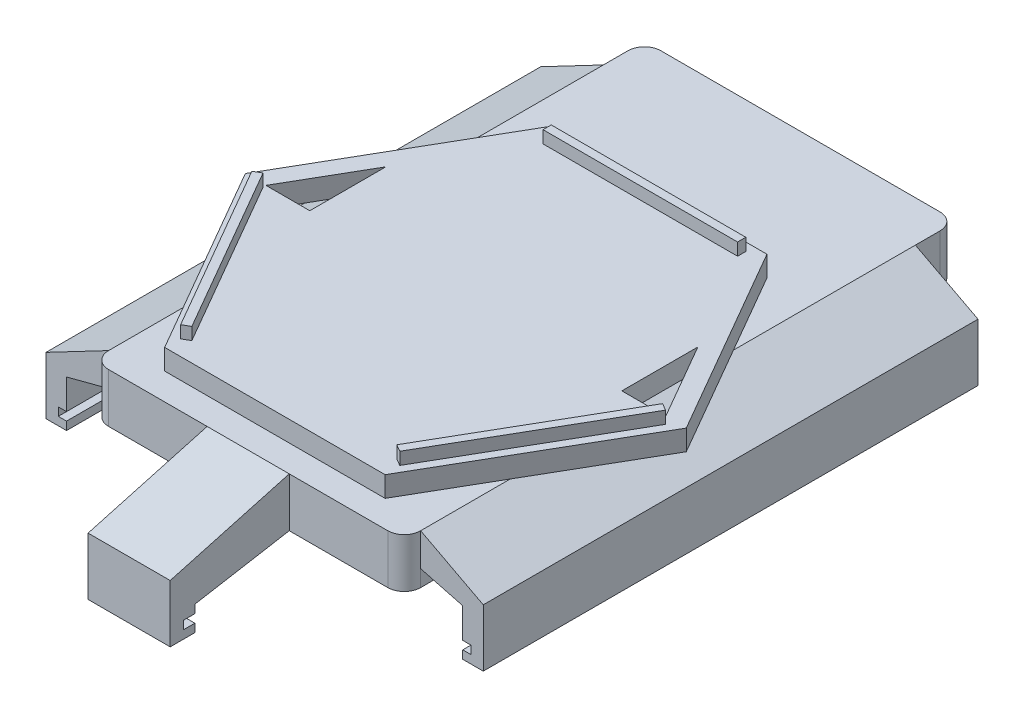
SolidWorks part; units mm, degrees
ref_plane "Plano frontal" through (0, 0, 0) normal (0, 0, 1) x (1, 0, 0)
ref_plane "Plano superior" through (0, 0, 0) normal (0, 1, 0) x (1, 0, 0)
ref_plane "Plano direito" through (0, 0, 0) normal (1, 0, 0) x (0, 0, -1)
sketch "Esboço1" plane through (0, 0, 0) normal (0, 1, 0) x (1, 0, 0)
  line L7 (53.6936, 0) -> (26.8468, 46.5)
  line L8 (26.8468, 46.5) -> (-26.8468, 46.5)
  line L9 (-26.8468, 46.5) -> (-53.6936, 0)
  line L10 (-53.6936, 0) -> (-26.8468, -46.5)
  line L11 (-26.8468, -46.5) -> (26.8468, -46.5)
  line L12 (26.8468, -46.5) -> (53.6936, 0)
  circle A1 centre (0, 0) radius 46.5 construction
extrude "Ressalto-extrusão1" add sketch "Esboço1" along normal blind 3
sketch "Esboço2" plane through (0, 3, 0) normal (0, 1, 0) x (1, 0, 0)
  line L2 (23.6921, 44.5) -> (-23.6921, 44.5)
  line L4 (-50.3842, -1.7321) -> (-26.6921, -42.7679)
  line L6 (26.6921, -42.7679) -> (50.3842, -1.7321)
  line L8 (-23.6921, 44.5) -> (-23.6921, 42.5)
  line L11 (23.6921, 44.5) -> (23.6921, 42.5)
  line L15 (50.3842, -1.7321) -> (48.6521, -0.7321)
  line L18 (26.6921, -42.7679) -> (24.96, -41.7679)
  line L20 (-48.6521, -0.7321) -> (-24.96, -41.7679)
  line L22 (-26.6921, -42.7679) -> (-24.96, -41.7679)
  line L25 (-50.3842, -1.7321) -> (-48.6521, -0.7321)
  line L36 (24.96, -41.7679) -> (48.6521, -0.7321)
  line L38 (23.6921, 42.5) -> (-23.6921, 42.5)
  line L40 (51.3842, 0) -> (25.6921, 44.5) [skipped]
  line L41 (-25.6921, 44.5) -> (-51.3842, 0) [skipped]
  line L42 (-25.6921, -44.5) -> (25.6921, -44.5) [skipped]
extrude "Ressalto-extrusão2" add sketch "Esboço2" along normal blind 3
sketch "Esboço3" plane through (0, 0, 0) normal (0, -1, 0) x (1, 0, 0)
  line L13 (26.8468, 46.5) -> (-26.8468, 46.5)
  line L14 (-26.8468, 46.5) -> (-53.6936, 0)
  line L15 (-53.6936, 0) -> (-26.8468, -46.5)
  line L16 (-26.8468, -46.5) -> (26.8468, -46.5)
  line L17 (26.8468, -46.5) -> (53.6936, 0)
  line L18 (53.6936, 0) -> (26.8468, 46.5)
  circle A0 centre (0, 0) radius 46.5 construction
extrude "Ressalto-extrusão3" add sketch "Esboço3" along normal blind 2
sketch "Esboço5" plane through (0, -2, 0) normal (0, -1, 0) x (1, 0, 0)
  line L1 (38, 49.0015) -> (38, -77.5)
  line L13 (-34, -81.5) -> (34, -81.5)
  line L15 (-34, 53.0015) -> (34, 53.0015)
  line L17 (-38, 49.0015) -> (-38, -77.5)
  arc A0 (38, 49.0015) -> (34, 53.0015) centre (34, 49.0015) ccw
  arc A1 (-34, 53.0015) -> (-38, 49.0015) centre (-34, 49.0015) ccw
  arc A2 (-38, -77.5) -> (-34, -81.5) centre (-34, -77.5) ccw
  arc A3 (34, -81.5) -> (38, -77.5) centre (34, -77.5) ccw
extrude "Ressalto-extrusão5" add sketch "Esboço5" along normal blind 12
sketch "Esboço7" plane through (0, 0, -81.5) normal (0, 0, -1) x (-1, 0, 0)
  line L6 (-34.2, -3) -> (34.2, -3)
  line L8 (-34.2, -3) -> (-34.2, -12.3)
  line L9 (34.2, -3) -> (34.2, -12.3)
  line L10 (31.2, -12.3) -> (34.2, -12.3)
  line L11 (-31.2, -12.3) -> (-34.2, -12.3)
  line L17 (-31.2, -26.2504) -> (31.2, -23.2814)
  line L18 (-31.2, -12.3) -> (-31.2, -26.2504)
  line L19 (31.2, -12.3) -> (31.2, -23.2814)
extrude "Corte-extrusão1" cut sketch "Esboço7" against normal blind 131
sketch "Esboço8" plane through (0, -2, 0) normal (0, -1, 0) x (1, 0, 0)
  line L6 (-48.6936, 0) -> (-38, 0)
  line L7 (38, 0) -> (48.6936, 0)
  line L8 (-48.6936, 0) -> (-38, -18.5218)
  line L10 (38, -18.5218) -> (48.6936, 0)
  line L12 (-38, 0) -> (-38, -18.5218)
  line L13 (38, 0) -> (38, -18.5218)
extrude "Corte-extrusão3" cut sketch "Esboço8" against normal blind 10
ref_plane "Plano3" through (0, 0, -71.5) normal (0, 0, -1) x (-1, 0, 0)
sketch "Esboço17" plane through (0, 0, -71.5) normal (0, 0, -1) x (-1, 0, 0)
  line L3 (-53.25, -20) -> (-53.25, -18)
  line L4 (-53.25, -18) -> (-53.25, -10)
  line L7 (-48.25, -18) -> (-48.25, -20)
  line L9 (53.25, -20) -> (53.25, -18)
  line L13 (48.25, -18) -> (48.25, -20)
  line L14 (53.25, -18) -> (53.25, -10)
  line L15 (-48.25, -22) -> (-48.25, -24)
  line L16 (48.25, -22) -> (48.25, -24)
  line L18 (-53.25, -20) -> (-53.25, -22)
  line L20 (-53.25, -22) -> (-53.25, -24)
  line L21 (-53.25, -24) -> (-48.25, -24)
  line L22 (48.25, -22) -> (48.25, -20)
  line L23 (53.25, -20) -> (53.25, -24)
  line L24 (48.25, -24) -> (53.25, -24)
  line L29 (-38, -6) -> (-38, -10)
  line L30 (38, -6) -> (38, -10)
  line L31 (-48.25, -22) -> (-48.25, -20)
  line L34 (-48.25, -12.6885) -> (-38, -10)
  line L35 (48.25, -12.6885) -> (38, -10)
  line L36 (-48.25, -18) -> (-48.25, -12.6885)
  line L37 (48.25, -18) -> (48.25, -12.6885)
  line L38 (53.25, -10) -> (38, -2)
  line L39 (38, -2) -> (38, -6)
  line L40 (-53.25, -10) -> (-38, -2)
  line L41 (-38, -2) -> (-38, -6)
extrude "Ressalto-extrusão13" add sketch "Esboço17" against normal blind 120.5
sketch "Esboço19" plane through (0, 0, 0) normal (1, 0, 0) x (0, 0, -1)
  line L0 (-53.0015, -14) -> (-53.0015, -2)
  line L1 (-76, -24) -> (-82, -24)
  line L2 (-82, -24) -> (-82, -10)
  line L4 (-82, -10) -> (-53.0015, -2)
  line L10 (-76, -24) -> (-76, -18)
  line L13 (-76, -18) -> (-53.0015, -14)
extrude "Ressalto-extrusão14" add sketch "Esboço19" along normal mid plane 20
sketch "Esboço20" plane through (0, 0, -71.5) normal (0, 0, -1) x (-1, 0, 0)
  line L2 (-50.25, -22) -> (50.25, -22)
  line L4 (-50.25, -20) -> (50.25, -20)
  line L7 (-50.25, -22) -> (-50.25, -20)
  line L10 (50.25, -22) -> (50.25, -20)
extrude "Corte-extrusão6" cut sketch "Esboço20" against normal blind 150.3
ref_plane "Plano4" through (34, -3, -81.5) normal (1, 0, 0) x (0, 0, -1)
